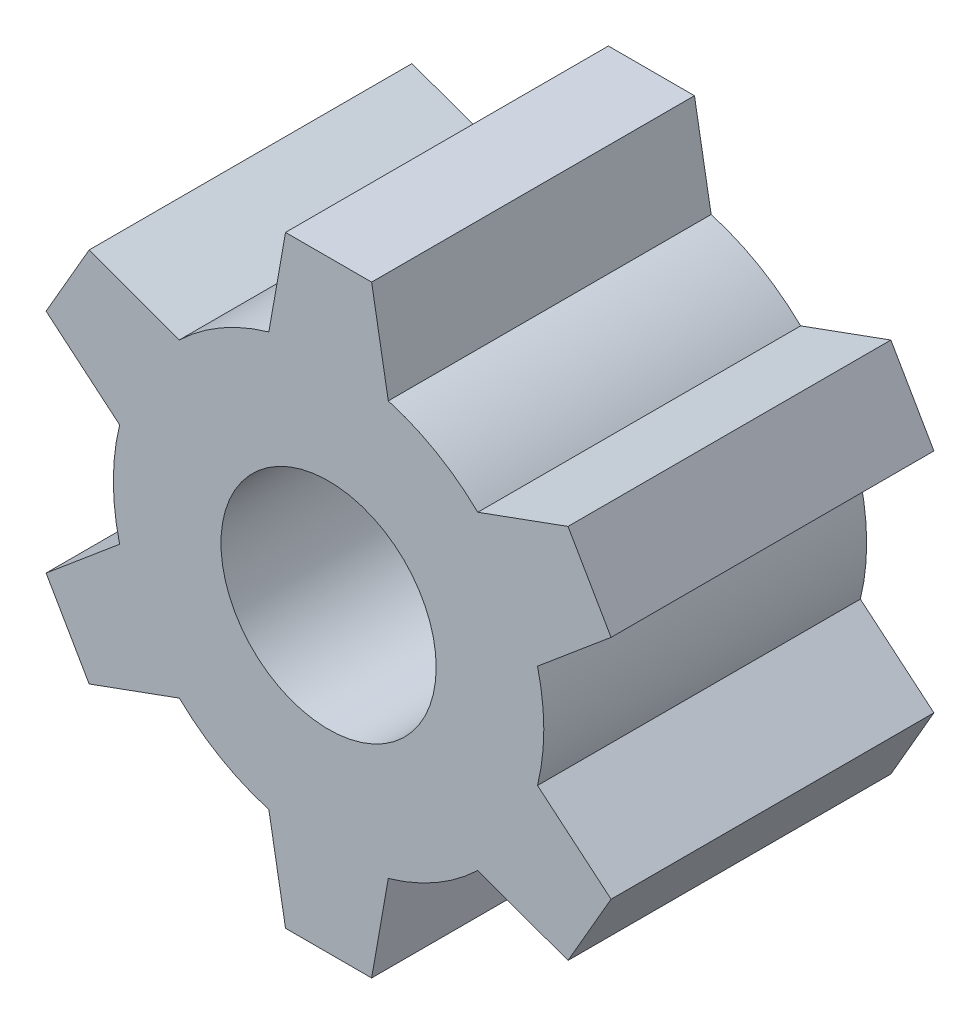
SolidWorks part; units mm, degrees
ref_plane "Alzado" through (0, 0, 0) normal (0, 0, 1) x (1, 0, 0)
ref_plane "Planta" through (0, 0, 0) normal (0, 1, 0) x (1, 0, 0)
ref_plane "Vista lateral" through (0, 0, 0) normal (1, 0, 0) x (0, 0, -1)
sketch "Croquis1" plane through (0, 0, 0) normal (0, 0, 1) x (1, 0, 0)
  line L0 (-1, 7) -> (1, 7)
  line L4 (-1, 7) -> (-1.3871, 4.8038)
  line L5 (1, 7) -> (1.3871, 4.8038)
  line L6 (5.5622, 4.366) -> (3.4666, 3.6031)
  line L7 (5.5622, 4.366) -> (6.5622, 2.634)
  line L8 (6.5622, 2.634) -> (4.8537, 1.2007)
  line L9 (6.5622, -2.634) -> (4.8537, -1.2007)
  line L10 (6.5622, -2.634) -> (5.5622, -4.366)
  line L11 (5.5622, -4.366) -> (3.4666, -3.6031)
  line L12 (1, -7) -> (1.3871, -4.8038)
  line L13 (1, -7) -> (-1, -7)
  line L14 (-1, -7) -> (-1.3871, -4.8038)
  line L15 (-5.5622, -4.366) -> (-3.4666, -3.6031)
  line L16 (-5.5622, -4.366) -> (-6.5622, -2.634)
  line L17 (-6.5622, -2.634) -> (-4.8537, -1.2007)
  line L18 (-6.5622, 2.634) -> (-4.8537, 1.2007)
  line L19 (-6.5622, 2.634) -> (-5.5622, 4.366)
  line L20 (-5.5622, 4.366) -> (-3.4666, 3.6031)
  arc A0 (-1.3871, 4.8038) -> (-3.4666, 3.6031) centre (0, 0) ccw
  circle A1 centre (0, 0) radius 2.5
  arc A2 (-4.8537, 1.2007) -> (-4.8537, -1.2007) centre (0, 0) ccw
  arc A3 (-3.4666, -3.6031) -> (-1.3871, -4.8038) centre (0, 0) ccw
  arc A4 (1.3871, -4.8038) -> (3.4666, -3.6031) centre (0, 0) ccw
  arc A5 (4.8537, -1.2007) -> (4.8537, 1.2007) centre (0, 0) ccw
  arc A6 (3.4666, 3.6031) -> (1.3871, 4.8038) centre (0, 0) ccw
  point P29 (0, 0)
  dimension "D1" = 6
extrude "Saliente-Extruir5" add sketch "Croquis1" along normal blind 7.5
